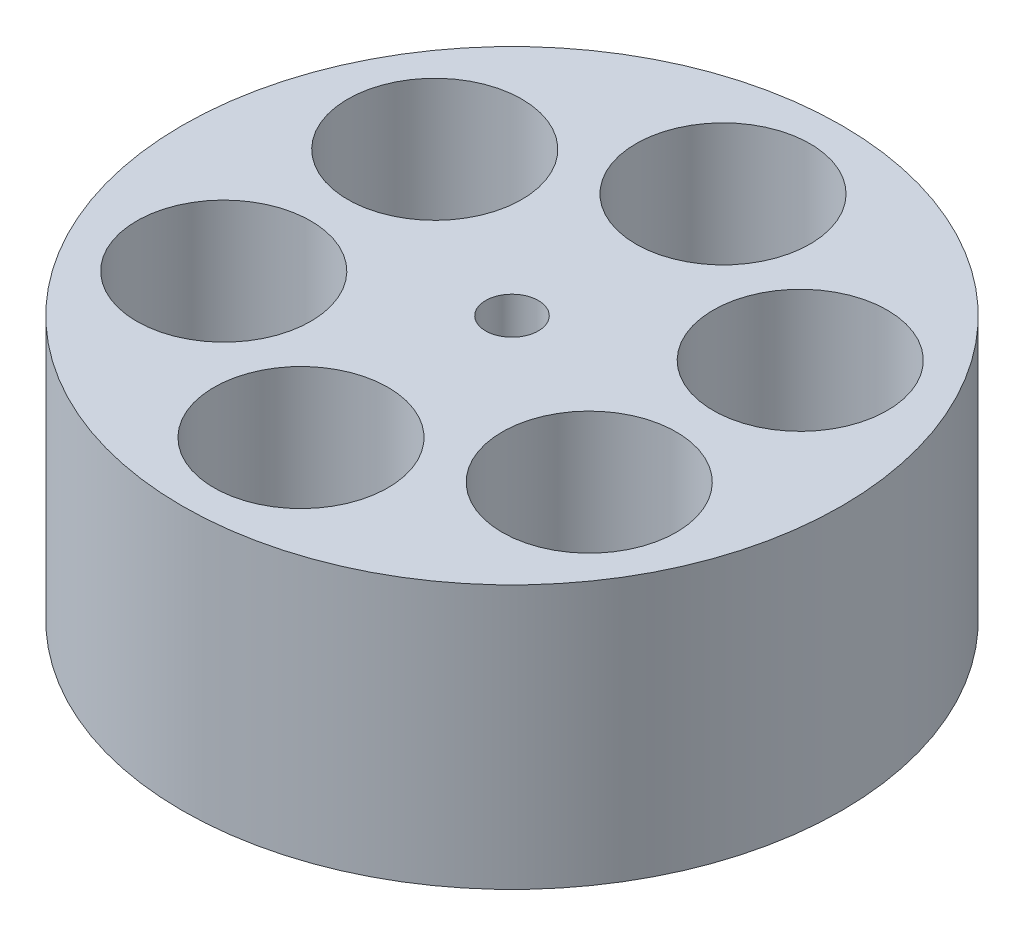
SolidWorks part; units mm, degrees
ref_plane "Front Plane" through (0, 0, 0) normal (0, 0, 1) x (1, 0, 0)
ref_plane "Top Plane" through (0, 0, 0) normal (0, 1, 0) x (1, 0, 0)
ref_plane "Right Plane" through (0, 0, 0) normal (1, 0, 0) x (0, 0, -1)
sketch "Sketch1" plane through (0, 0, 0) normal (0, 1, 0) x (1, 0, 0)
  circle A0 centre (0, 0) radius 25
  dimension "D1" = 50
extrude "Boss-Extrude1" add sketch "Sketch1" along normal blind 20
sketch "Sketch2" plane through (0, 20, 0) normal (0, 1, 0) x (1, 0, 0)
  line L0 (0, -11) -> (0, 11) construction
  line L1 (-11, 0) -> (11, 0) construction
  line L2 (0, 22.6) -> (16.0728, 22.6) construction
  line L3 (0, 25) -> (15.4299, 25) construction
  circle A0 centre (0, 16) radius 6.6
  circle A1 centre (0, 0) radius 25 construction
  dimension "D1" = 13.2
  dimension "D2" = 16
  dimension "D3" = 2.4
extrude "Cut-Extrude1" cut sketch "Sketch2" against normal blind 10
sketch "Sketch3" plane through (0, 10, 0) normal (0, 1, 0) x (1, 0, 0)
  circle A0 centre (0, 16) radius 2
  dimension "D1" = 4
extrude "Cut-Extrude2" cut sketch "Sketch3" against normal blind 35
pattern_circular "CirPattern1" count 6 over 360 about axis through (0, 0, 0) along (0, 1, 0) of "Cut-Extrude1", "Cut-Extrude2"
sketch "Sketch5" plane through (0, 0, 0) normal (0, 0, 1) x (1, 0, 0)
  line L0 (0, 20) -> (-2, 20)
  line L1 (6.6, 20) -> (-6.6, 20) construction
  line L2 (25, 20) -> (-25, 20) construction
  line L3 (-2, 20) -> (-2, 7)
  line L4 (-2, 7) -> (-5, 4)
  line L5 (-5, 4) -> (-5, 0)
  line L6 (27.5, 0) -> (-27.5, 0) construction
  line L7 (-5, 0) -> (0, 0)
  line L8 (0, 0) -> (0, 20)
  line L9 (0, 26.0355) -> (0, -8.4643) construction
  dimension "D1" = 2
  dimension "D2" = 5
  dimension "D3" = 4
  dimension "D4" = 45
revolve "Cut-Revolve1" cut sketch "Sketch5" angle 360 about L9
